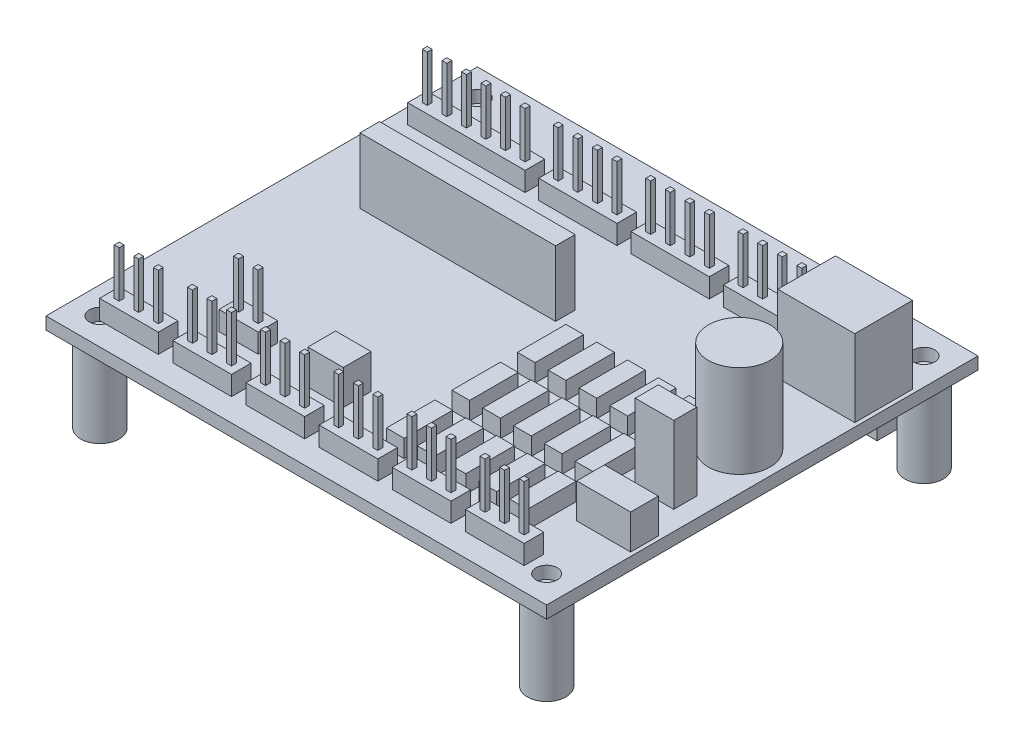
SolidWorks part; units mm, degrees
ref_plane "Front Plane" through (0, 0, 0) normal (0, 0, 1) x (1, 0, 0)
ref_plane "Top Plane" through (0, 0, 0) normal (0, 1, 0) x (1, 0, 0)
ref_plane "Right Plane" through (0, 0, 0) normal (1, 0, 0) x (0, 0, -1)
sketch "SK PCB 65x56" plane through (0, 0, 0) normal (0, 1, 0) x (1, 0, 0)
  line L1 (0, 56) -> (65, 56)
  line L2 (0, 56) -> (0, 0)
  line L3 (0, 0) -> (65, 0)
  line L4 (65, 56) -> (65, 0)
  circle A0 centre (3.5, 3.5) radius 1.375
  circle A1 centre (61.5, 3.5) radius 1.375
  circle A2 centre (3.5, 52.5) radius 1.375
  circle A3 centre (61.5, 52.5) radius 1.375
extrude "PCB 65x56" add sketch "SK PCB 65x56" along normal blind 1.6 separate body
sketch "SK Standoffs M2.5x11" plane through (0, 0, 0) normal (0, 1, 0) x (1, 0, 0)
  circle A0 centre (3.5, 3.5) radius 2.5
  circle A1 centre (61.5, 3.5) radius 2.5
  circle A2 centre (3.5, 52.5) radius 2.5
  circle A3 centre (61.5, 52.5) radius 2.5
extrude "Standoffs M2.5x11" add sketch "SK Standoffs M2.5x11" along normal blind 11 from offset 11 separate body
sketch "SK GPIO female header 2x20" plane through (0, 0, 0) normal (0, 1, 0) x (1, 0, 0)
  line L1 (7.1, 55.1) -> (57.9, 55.1)
  line L2 (7.1, 55.1) -> (7.1, 50)
  line L3 (7.1, 50) -> (57.9, 50)
  line L4 (57.9, 55.1) -> (57.9, 50)
extrude "GPIO female header 2x20" add sketch "SK GPIO female header 2x20" along normal blind 8.5 from offset 8.5 separate body
sketch "SK Back headers J2-J6 J10" plane through (0, 0, 0) normal (0, 1, 0) x (1, 0, 0)
  line L1 (4, 5.5) -> (11.62, 5.5)
  line L2 (4, 5.5) -> (4, 2.96)
  line L3 (4, 2.96) -> (11.62, 2.96)
  line L4 (11.62, 5.5) -> (11.62, 2.96)
  line L6 (13.5, 5.5) -> (21.12, 5.5)
  line L7 (13.5, 5.5) -> (13.5, 2.96)
  line L8 (13.5, 2.96) -> (21.12, 2.96)
  line L9 (21.12, 5.5) -> (21.12, 2.96)
  line L11 (23, 5.5) -> (30.62, 5.5)
  line L12 (23, 5.5) -> (23, 2.96)
  line L13 (23, 2.96) -> (30.62, 2.96)
  line L14 (30.62, 5.5) -> (30.62, 2.96)
  line L16 (32.5, 5.5) -> (40.12, 5.5)
  line L17 (32.5, 5.5) -> (32.5, 2.96)
  line L18 (32.5, 2.96) -> (40.12, 2.96)
  line L19 (40.12, 5.5) -> (40.12, 2.96)
  line L21 (42, 5.5) -> (49.62, 5.5)
  line L22 (42, 5.5) -> (42, 2.96)
  line L23 (42, 2.96) -> (49.62, 2.96)
  line L24 (49.62, 5.5) -> (49.62, 2.96)
  line L26 (51.5, 5.5) -> (59.12, 5.5)
  line L27 (51.5, 5.5) -> (51.5, 2.96)
  line L28 (51.5, 2.96) -> (59.12, 2.96)
  line L29 (59.12, 5.5) -> (59.12, 2.96)
extrude "Back headers J2-J6 J10" add sketch "SK Back headers J2-J6 J10" along normal blind 2.5 from offset 1.6 separate body
sketch "SK Back header pins" plane through (0, 0, 0) normal (0, 1, 0) x (1, 0, 0)
  line L1 (4.95, 4.55) -> (5.59, 4.55)
  line L2 (4.95, 4.55) -> (4.95, 3.91)
  line L3 (4.95, 3.91) -> (5.59, 3.91)
  line L4 (5.59, 4.55) -> (5.59, 3.91)
  line L6 (7.49, 4.55) -> (8.13, 4.55)
  line L7 (7.49, 4.55) -> (7.49, 3.91)
  line L8 (7.49, 3.91) -> (8.13, 3.91)
  line L9 (8.13, 4.55) -> (8.13, 3.91)
  line L11 (10.03, 4.55) -> (10.67, 4.55)
  line L12 (10.03, 4.55) -> (10.03, 3.91)
  line L13 (10.03, 3.91) -> (10.67, 3.91)
  line L14 (10.67, 4.55) -> (10.67, 3.91)
  line L16 (14.45, 4.55) -> (15.09, 4.55)
  line L17 (14.45, 4.55) -> (14.45, 3.91)
  line L18 (14.45, 3.91) -> (15.09, 3.91)
  line L19 (15.09, 4.55) -> (15.09, 3.91)
  line L21 (16.99, 4.55) -> (17.63, 4.55)
  line L22 (16.99, 4.55) -> (16.99, 3.91)
  line L23 (16.99, 3.91) -> (17.63, 3.91)
  line L24 (17.63, 4.55) -> (17.63, 3.91)
  line L26 (19.53, 4.55) -> (20.17, 4.55)
  line L27 (19.53, 4.55) -> (19.53, 3.91)
  line L28 (19.53, 3.91) -> (20.17, 3.91)
  line L29 (20.17, 4.55) -> (20.17, 3.91)
  line L31 (23.95, 4.55) -> (24.59, 4.55)
  line L32 (23.95, 4.55) -> (23.95, 3.91)
  line L33 (23.95, 3.91) -> (24.59, 3.91)
  line L34 (24.59, 4.55) -> (24.59, 3.91)
  line L36 (26.49, 4.55) -> (27.13, 4.55)
  line L37 (26.49, 4.55) -> (26.49, 3.91)
  line L38 (26.49, 3.91) -> (27.13, 3.91)
  line L39 (27.13, 4.55) -> (27.13, 3.91)
  line L41 (29.03, 4.55) -> (29.67, 4.55)
  line L42 (29.03, 4.55) -> (29.03, 3.91)
  line L43 (29.03, 3.91) -> (29.67, 3.91)
  line L44 (29.67, 4.55) -> (29.67, 3.91)
  line L46 (33.45, 4.55) -> (34.09, 4.55)
  line L47 (33.45, 4.55) -> (33.45, 3.91)
  line L48 (33.45, 3.91) -> (34.09, 3.91)
  line L49 (34.09, 4.55) -> (34.09, 3.91)
  line L51 (35.99, 4.55) -> (36.63, 4.55)
  line L52 (35.99, 4.55) -> (35.99, 3.91)
  line L53 (35.99, 3.91) -> (36.63, 3.91)
  line L54 (36.63, 4.55) -> (36.63, 3.91)
  line L56 (38.53, 4.55) -> (39.17, 4.55)
  line L57 (38.53, 4.55) -> (38.53, 3.91)
  line L58 (38.53, 3.91) -> (39.17, 3.91)
  line L59 (39.17, 4.55) -> (39.17, 3.91)
  line L61 (42.95, 4.55) -> (43.59, 4.55)
  line L62 (42.95, 4.55) -> (42.95, 3.91)
  line L63 (42.95, 3.91) -> (43.59, 3.91)
  line L64 (43.59, 4.55) -> (43.59, 3.91)
  line L66 (45.49, 4.55) -> (46.13, 4.55)
  line L67 (45.49, 4.55) -> (45.49, 3.91)
  line L68 (45.49, 3.91) -> (46.13, 3.91)
  line L69 (46.13, 4.55) -> (46.13, 3.91)
  line L71 (48.03, 4.55) -> (48.67, 4.55)
  line L72 (48.03, 4.55) -> (48.03, 3.91)
  line L73 (48.03, 3.91) -> (48.67, 3.91)
  line L74 (48.67, 4.55) -> (48.67, 3.91)
  line L76 (52.45, 4.55) -> (53.09, 4.55)
  line L77 (52.45, 4.55) -> (52.45, 3.91)
  line L78 (52.45, 3.91) -> (53.09, 3.91)
  line L79 (53.09, 4.55) -> (53.09, 3.91)
  line L81 (54.99, 4.55) -> (55.63, 4.55)
  line L82 (54.99, 4.55) -> (54.99, 3.91)
  line L83 (54.99, 3.91) -> (55.63, 3.91)
  line L84 (55.63, 4.55) -> (55.63, 3.91)
  line L86 (57.53, 4.55) -> (58.17, 4.55)
  line L87 (57.53, 4.55) -> (57.53, 3.91)
  line L88 (57.53, 3.91) -> (58.17, 3.91)
  line L89 (58.17, 4.55) -> (58.17, 3.91)
extrude "Back header pins" add sketch "SK Back header pins" along normal blind 6 from offset 4.1 separate body
sketch "SK Front headers J7 J8 J9 J11" plane through (0, 0, 0) normal (0, 1, 0) x (1, 0, 0)
  line L1 (2, 47.5) -> (17.24, 47.5)
  line L2 (2, 47.5) -> (2, 44.96)
  line L3 (2, 44.96) -> (17.24, 44.96)
  line L4 (17.24, 47.5) -> (17.24, 44.96)
  line L6 (19, 47.5) -> (29.16, 47.5)
  line L7 (19, 47.5) -> (19, 44.96)
  line L8 (19, 44.96) -> (29.16, 44.96)
  line L9 (29.16, 47.5) -> (29.16, 44.96)
  line L11 (31, 47.5) -> (41.16, 47.5)
  line L12 (31, 47.5) -> (31, 44.96)
  line L13 (31, 44.96) -> (41.16, 44.96)
  line L14 (41.16, 47.5) -> (41.16, 44.96)
  line L16 (43, 47.5) -> (53.16, 47.5)
  line L17 (43, 47.5) -> (43, 44.96)
  line L18 (43, 44.96) -> (53.16, 44.96)
  line L19 (53.16, 47.5) -> (53.16, 44.96)
  line L21 (13, 12) -> (18.08, 12)
  line L22 (13, 12) -> (13, 9.46)
  line L23 (13, 9.46) -> (18.08, 9.46)
  line L24 (18.08, 12) -> (18.08, 9.46)
extrude "Front headers J7 J8 J9 J11" add sketch "SK Front headers J7 J8 J9 J11" along normal blind 2.5 from offset 1.6 separate body
sketch "SK Front header pins" plane through (0, 0, 0) normal (0, 1, 0) x (1, 0, 0)
  line L1 (2.95, 46.55) -> (3.59, 46.55)
  line L2 (2.95, 46.55) -> (2.95, 45.91)
  line L3 (2.95, 45.91) -> (3.59, 45.91)
  line L4 (3.59, 46.55) -> (3.59, 45.91)
  line L6 (5.49, 46.55) -> (6.13, 46.55)
  line L7 (5.49, 46.55) -> (5.49, 45.91)
  line L8 (5.49, 45.91) -> (6.13, 45.91)
  line L9 (6.13, 46.55) -> (6.13, 45.91)
  line L11 (8.03, 46.55) -> (8.67, 46.55)
  line L12 (8.03, 46.55) -> (8.03, 45.91)
  line L13 (8.03, 45.91) -> (8.67, 45.91)
  line L14 (8.67, 46.55) -> (8.67, 45.91)
  line L16 (10.57, 46.55) -> (11.21, 46.55)
  line L17 (10.57, 46.55) -> (10.57, 45.91)
  line L18 (10.57, 45.91) -> (11.21, 45.91)
  line L19 (11.21, 46.55) -> (11.21, 45.91)
  line L21 (13.11, 46.55) -> (13.75, 46.55)
  line L22 (13.11, 46.55) -> (13.11, 45.91)
  line L23 (13.11, 45.91) -> (13.75, 45.91)
  line L24 (13.75, 46.55) -> (13.75, 45.91)
  line L26 (15.65, 46.55) -> (16.29, 46.55)
  line L27 (15.65, 46.55) -> (15.65, 45.91)
  line L28 (15.65, 45.91) -> (16.29, 45.91)
  line L29 (16.29, 46.55) -> (16.29, 45.91)
  line L31 (19.95, 46.55) -> (20.59, 46.55)
  line L32 (19.95, 46.55) -> (19.95, 45.91)
  line L33 (19.95, 45.91) -> (20.59, 45.91)
  line L34 (20.59, 46.55) -> (20.59, 45.91)
  line L36 (22.49, 46.55) -> (23.13, 46.55)
  line L37 (22.49, 46.55) -> (22.49, 45.91)
  line L38 (22.49, 45.91) -> (23.13, 45.91)
  line L39 (23.13, 46.55) -> (23.13, 45.91)
  line L41 (25.03, 46.55) -> (25.67, 46.55)
  line L42 (25.03, 46.55) -> (25.03, 45.91)
  line L43 (25.03, 45.91) -> (25.67, 45.91)
  line L44 (25.67, 46.55) -> (25.67, 45.91)
  line L46 (27.57, 46.55) -> (28.21, 46.55)
  line L47 (27.57, 46.55) -> (27.57, 45.91)
  line L48 (27.57, 45.91) -> (28.21, 45.91)
  line L49 (28.21, 46.55) -> (28.21, 45.91)
  line L51 (31.95, 46.55) -> (32.59, 46.55)
  line L52 (31.95, 46.55) -> (31.95, 45.91)
  line L53 (31.95, 45.91) -> (32.59, 45.91)
  line L54 (32.59, 46.55) -> (32.59, 45.91)
  line L56 (34.49, 46.55) -> (35.13, 46.55)
  line L57 (34.49, 46.55) -> (34.49, 45.91)
  line L58 (34.49, 45.91) -> (35.13, 45.91)
  line L59 (35.13, 46.55) -> (35.13, 45.91)
  line L61 (37.03, 46.55) -> (37.67, 46.55)
  line L62 (37.03, 46.55) -> (37.03, 45.91)
  line L63 (37.03, 45.91) -> (37.67, 45.91)
  line L64 (37.67, 46.55) -> (37.67, 45.91)
  line L66 (39.57, 46.55) -> (40.21, 46.55)
  line L67 (39.57, 46.55) -> (39.57, 45.91)
  line L68 (39.57, 45.91) -> (40.21, 45.91)
  line L69 (40.21, 46.55) -> (40.21, 45.91)
  line L71 (43.95, 46.55) -> (44.59, 46.55)
  line L72 (43.95, 46.55) -> (43.95, 45.91)
  line L73 (43.95, 45.91) -> (44.59, 45.91)
  line L74 (44.59, 46.55) -> (44.59, 45.91)
  line L76 (46.49, 46.55) -> (47.13, 46.55)
  line L77 (46.49, 46.55) -> (46.49, 45.91)
  line L78 (46.49, 45.91) -> (47.13, 45.91)
  line L79 (47.13, 46.55) -> (47.13, 45.91)
  line L81 (49.03, 46.55) -> (49.67, 46.55)
  line L82 (49.03, 46.55) -> (49.03, 45.91)
  line L83 (49.03, 45.91) -> (49.67, 45.91)
  line L84 (49.67, 46.55) -> (49.67, 45.91)
  line L86 (51.57, 46.55) -> (52.21, 46.55)
  line L87 (51.57, 46.55) -> (51.57, 45.91)
  line L88 (51.57, 45.91) -> (52.21, 45.91)
  line L89 (52.21, 46.55) -> (52.21, 45.91)
  line L91 (13.95, 11.05) -> (14.59, 11.05)
  line L92 (13.95, 11.05) -> (13.95, 10.41)
  line L93 (13.95, 10.41) -> (14.59, 10.41)
  line L94 (14.59, 11.05) -> (14.59, 10.41)
  line L96 (16.49, 11.05) -> (17.13, 11.05)
  line L97 (16.49, 11.05) -> (16.49, 10.41)
  line L98 (16.49, 10.41) -> (17.13, 10.41)
  line L99 (17.13, 11.05) -> (17.13, 10.41)
extrude "Front header pins" add sketch "SK Front header pins" along normal blind 6 from offset 4.1 separate body
sketch "SK J1 5V screw terminal" plane through (0, 0, 0) normal (0, 1, 0) x (1, 0, 0)
  line L1 (54.5, 48) -> (64.5, 48)
  line L2 (54.5, 48) -> (54.5, 40.5)
  line L3 (54.5, 40.5) -> (64.5, 40.5)
  line L4 (64.5, 48) -> (64.5, 40.5)
extrude "J1 5V screw terminal" add sketch "SK J1 5V screw terminal" along normal blind 10 from offset 1.6 separate body
sketch "SK ADS1115 socket 1x10" plane through (0, 0, 0) normal (0, 1, 0) x (1, 0, 0)
  line L1 (8.3, 35) -> (33.7, 35)
  line L2 (8.3, 35) -> (8.3, 32.46)
  line L3 (8.3, 32.46) -> (33.7, 32.46)
  line L4 (33.7, 35) -> (33.7, 32.46)
extrude "ADS1115 socket 1x10" add sketch "SK ADS1115 socket 1x10" along normal blind 8.5 from offset 1.6 separate body
sketch "SK Resistors R1-R15" plane through (0, 0, 0) normal (0, 1, 0) x (1, 0, 0)
  line L1 (37, 30.5) -> (39.3, 30.5)
  line L2 (37, 30.5) -> (37, 24.2)
  line L3 (37, 24.2) -> (39.3, 24.2)
  line L4 (39.3, 30.5) -> (39.3, 24.2)
  line L6 (41, 30.5) -> (43.3, 30.5)
  line L7 (41, 30.5) -> (41, 24.2)
  line L8 (41, 24.2) -> (43.3, 24.2)
  line L9 (43.3, 30.5) -> (43.3, 24.2)
  line L11 (45, 30.5) -> (47.3, 30.5)
  line L12 (45, 30.5) -> (45, 24.2)
  line L13 (45, 24.2) -> (47.3, 24.2)
  line L14 (47.3, 30.5) -> (47.3, 24.2)
  line L16 (49, 30.5) -> (51.3, 30.5)
  line L17 (49, 30.5) -> (49, 24.2)
  line L18 (49, 24.2) -> (51.3, 24.2)
  line L19 (51.3, 30.5) -> (51.3, 24.2)
  line L21 (53, 30.5) -> (55.3, 30.5)
  line L22 (53, 30.5) -> (53, 24.2)
  line L23 (53, 24.2) -> (55.3, 24.2)
  line L24 (55.3, 30.5) -> (55.3, 24.2)
  line L26 (37, 22) -> (39.3, 22)
  line L27 (37, 22) -> (37, 15.7)
  line L28 (37, 15.7) -> (39.3, 15.7)
  line L29 (39.3, 22) -> (39.3, 15.7)
  line L31 (41, 22) -> (43.3, 22)
  line L32 (41, 22) -> (41, 15.7)
  line L33 (41, 15.7) -> (43.3, 15.7)
  line L34 (43.3, 22) -> (43.3, 15.7)
  line L36 (45, 22) -> (47.3, 22)
  line L37 (45, 22) -> (45, 15.7)
  line L38 (45, 15.7) -> (47.3, 15.7)
  line L39 (47.3, 22) -> (47.3, 15.7)
  line L41 (49, 22) -> (51.3, 22)
  line L42 (49, 22) -> (49, 15.7)
  line L43 (49, 15.7) -> (51.3, 15.7)
  line L44 (51.3, 22) -> (51.3, 15.7)
  line L46 (53, 22) -> (55.3, 22)
  line L47 (53, 22) -> (53, 15.7)
  line L48 (53, 15.7) -> (55.3, 15.7)
  line L49 (55.3, 22) -> (55.3, 15.7)
  line L51 (37, 13.5) -> (39.3, 13.5)
  line L52 (37, 13.5) -> (37, 7.2)
  line L53 (37, 7.2) -> (39.3, 7.2)
  line L54 (39.3, 13.5) -> (39.3, 7.2)
  line L56 (41, 13.5) -> (43.3, 13.5)
  line L57 (41, 13.5) -> (41, 7.2)
  line L58 (41, 7.2) -> (43.3, 7.2)
  line L59 (43.3, 13.5) -> (43.3, 7.2)
  line L61 (45, 13.5) -> (47.3, 13.5)
  line L62 (45, 13.5) -> (45, 7.2)
  line L63 (45, 7.2) -> (47.3, 7.2)
  line L64 (47.3, 13.5) -> (47.3, 7.2)
  line L66 (49, 13.5) -> (51.3, 13.5)
  line L67 (49, 13.5) -> (49, 7.2)
  line L68 (49, 7.2) -> (51.3, 7.2)
  line L69 (51.3, 13.5) -> (51.3, 7.2)
  line L71 (53, 13.5) -> (55.3, 13.5)
  line L72 (53, 13.5) -> (53, 7.2)
  line L73 (53, 7.2) -> (55.3, 7.2)
  line L74 (55.3, 13.5) -> (55.3, 7.2)
extrude "Resistors R1-R15" add sketch "SK Resistors R1-R15" along normal blind 2.3 from offset 1.6 separate body
sketch "SK C1 470uF" plane through (0, 0, 0) normal (0, 1, 0) x (1, 0, 0)
  circle A0 centre (60, 30) radius 4
extrude "C1 470uF" add sketch "SK C1 470uF" along normal blind 12 from offset 1.6 separate body
sketch "SK F1 PTC 2.5A" plane through (0, 0, 0) normal (0, 1, 0) x (1, 0, 0)
  line L1 (57.5, 22) -> (62.5, 22)
  line L2 (57.5, 22) -> (57.5, 19)
  line L3 (57.5, 19) -> (62.5, 19)
  line L4 (62.5, 22) -> (62.5, 19)
extrude "F1 PTC 2.5A" add sketch "SK F1 PTC 2.5A" along normal blind 10 from offset 1.6 separate body
sketch "SK D1 TVS and Q1 BC557" plane through (0, 0, 0) normal (0, 1, 0) x (1, 0, 0)
  line L1 (57.5, 15) -> (64.5, 15)
  line L2 (57.5, 15) -> (57.5, 11.4)
  line L3 (57.5, 11.4) -> (64.5, 11.4)
  line L4 (64.5, 15) -> (64.5, 11.4)
  line L6 (25, 12.6) -> (29.6, 12.6)
  line L7 (25, 12.6) -> (25, 9)
  line L8 (25, 9) -> (29.6, 9)
  line L9 (29.6, 12.6) -> (29.6, 9)
extrude "D1 TVS and Q1 BC557" add sketch "SK D1 TVS and Q1 BC557" along normal blind 4.5 from offset 1.6 separate body
